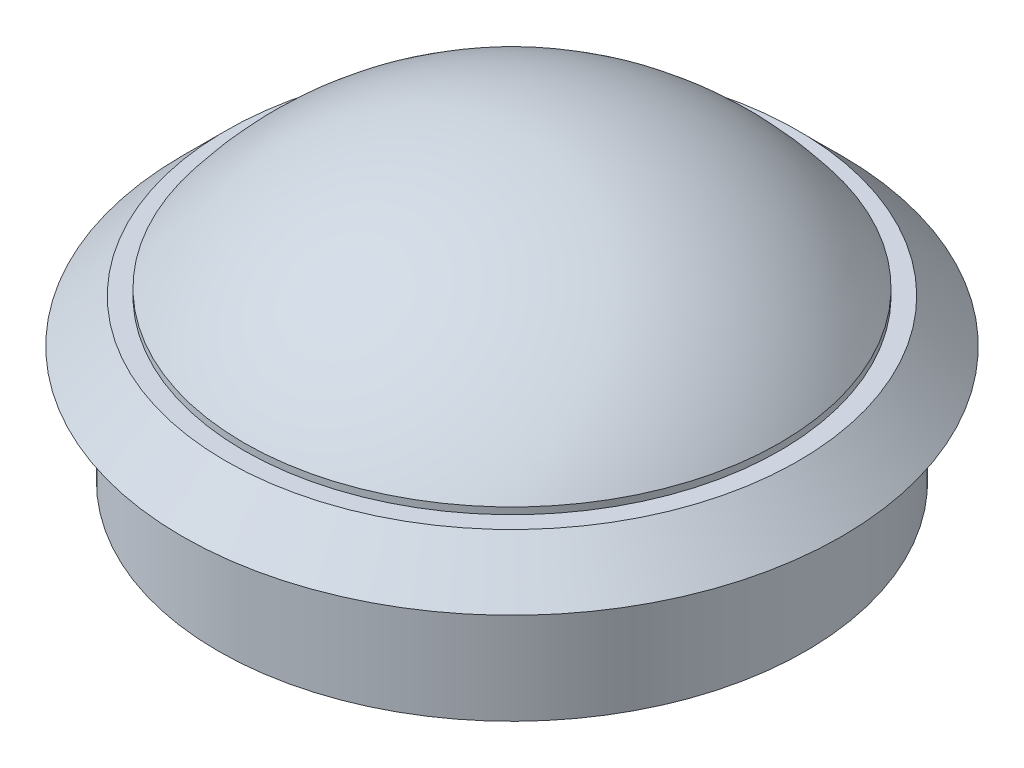
SolidWorks part; units mm, degrees
ref_plane "Front Plane" through (0, 0, 0) normal (0, 0, 1) x (1, 0, 0)
ref_plane "Top Plane" through (0, 0, 0) normal (0, 1, 0) x (1, 0, 0)
ref_plane "Right Plane" through (0, 0, 0) normal (1, 0, 0) x (0, 0, -1)
sketch "Sketch1" plane through (0, 0, 0) normal (0, 0, 1) x (1, 0, 0)
  line L0 (0, 50.071) -> (0, -17.0481) construction
  line L1 (-43.9, 0) -> (-43.9, 17.5)
  line L2 (-43.9, 17.5) -> (-49.25, 17.5)
  line L3 (-49.25, 17.5) -> (-42.75, 24)
  line L4 (-42.75, 24) -> (-40.0408, 24)
  line L5 (-40.0408, 24) -> (-40.0408, 25)
  line L6 (0, 45) -> (0, 0)
  line L7 (0, 0) -> (-43.9, 0)
  arc A0 (0, 45) -> (-40.0408, 25) centre (0, -5.0816) ccw
  point P10 (0, 0)
  point P13 (-40.1594, 25.3103)
  dimension "D1" = 87.8
  dimension "D2" = 17.5
  dimension "D3" = 45
  dimension "D4" = 98.5
  dimension "D5" = 21
  dimension "D6" = 6.5
  dimension "D7" = 1
  dimension "D8" = 80.0815
revolve "Revolve1" add sketch "Sketch1" angle 360 about L0
